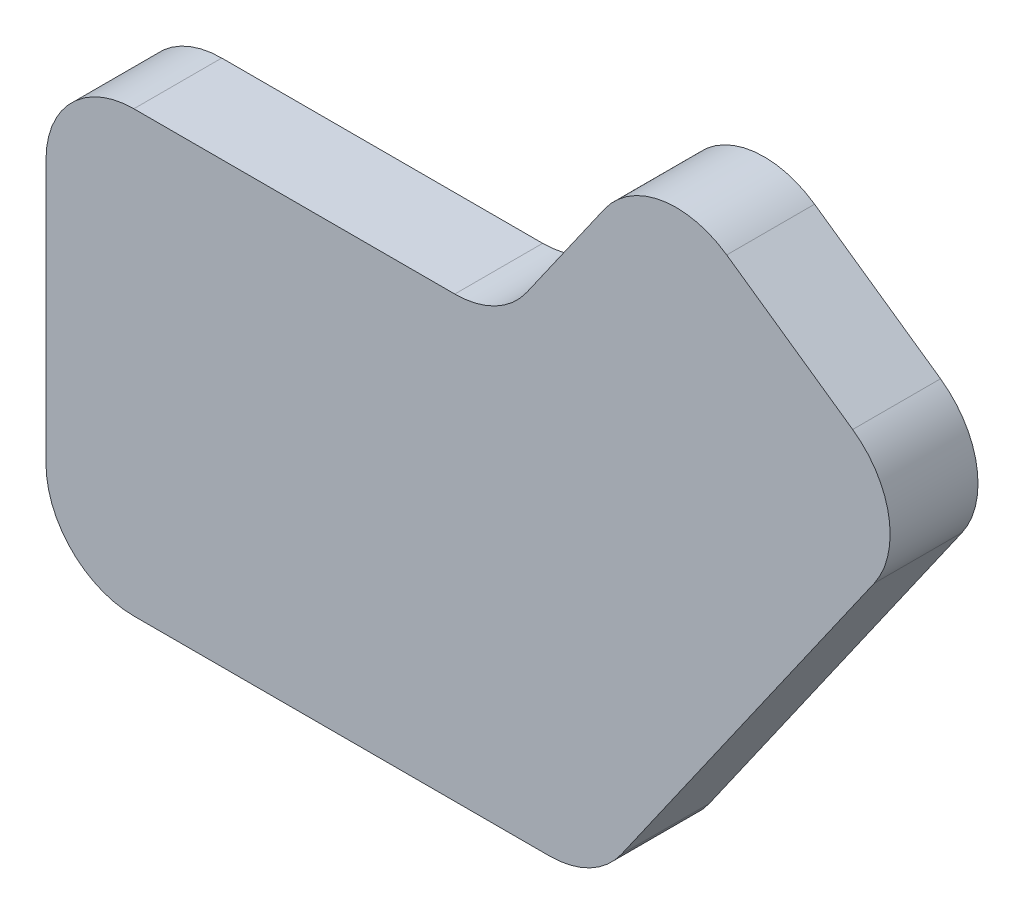
SolidWorks part; units mm, degrees
material "Alloy Steel"
ref_plane "Front Plane" through (0, 0, 0) normal (0, 0, 1) x (1, 0, 0)
ref_plane "Top Plane" through (0, 0, 0) normal (0, 1, 0) x (1, 0, 0)
ref_plane "Right Plane" through (0, 0, 0) normal (1, 0, 0) x (0, 0, -1)
sketch "Sketch1" plane through (0, 0, 0) normal (0, 0, 1) x (1, 0, 0)
  line L0 (0, 0) -> (-125, 0)
  line L1 (-125, 0) -> (-125, 100)
  line L2 (-125, 100) -> (-21.5373, 100)
  line L3 (0, 0) -> (75, 107.1111)
  line L4 (75, 107.1111) -> (13.5636, 150.1293)
  line L5 (13.5636, 150.1293) -> (-21.5373, 100)
  dimension "D1" = 125
  dimension "D2" = 200
  dimension "D3" = 125
  dimension "D4" = 100
  dimension "D5" = 75
extrude "Boss-Extrude1" add sketch "Sketch1" along normal blind 20
fillet "Fillet1" radius 20 6 edges at (-21.5373, 100, 10) (-125, 0, 10) (-125, 100, 10) (13.5636, 150.1293, 10) (75, 107.1111, 10) (0, 0, 10)
